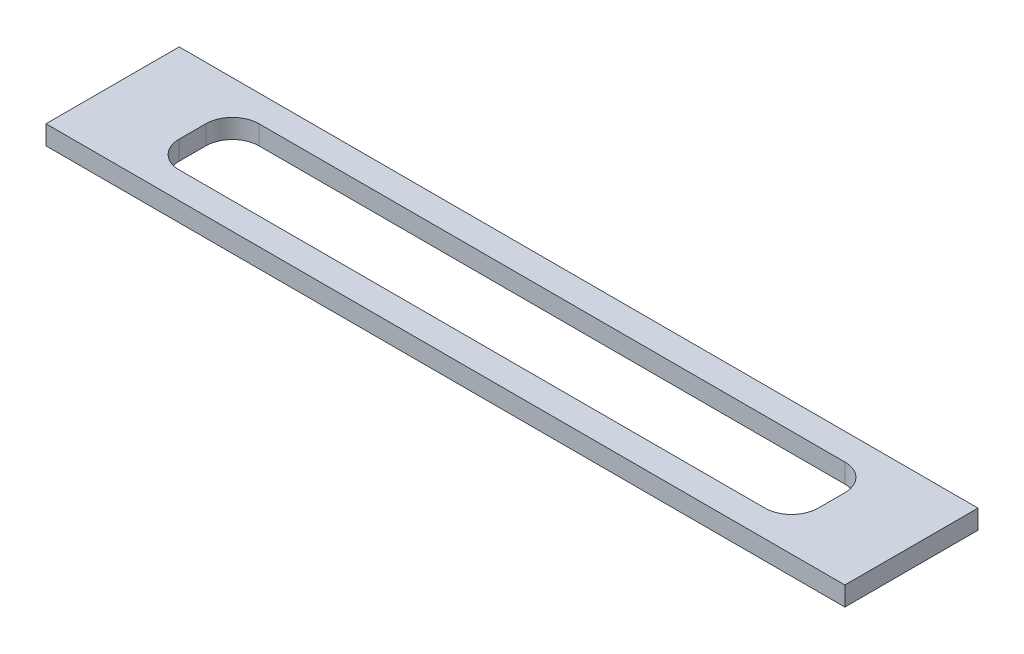
SolidWorks part; units mm, degrees
ref_plane "Front Plane" through (0, 0, 0) normal (0, 0, 1) x (1, 0, 0)
ref_plane "Top Plane" through (0, 0, 0) normal (0, 1, 0) x (1, 0, 0)
ref_plane "Right Plane" through (0, 0, 0) normal (1, 0, 0) x (0, 0, -1)
sketch "Sketch1" plane through (0, 0, 0) normal (0, 1, 0) x (1, 0, 0)
  line L1 (-691.8296, -43.3638) -> (70.1704, -43.3638)
  line L2 (-691.8296, -43.3638) -> (-691.8296, -170.3638)
  line L3 (-691.8296, -170.3638) -> (70.1704, -170.3638)
  line L4 (70.1704, -43.3638) -> (70.1704, -170.3638)
  dimension "D1" = 762
  dimension "D2" = 127
extrude "Boss-Extrude1" add sketch "Sketch1" along normal blind 18.288
sketch "Sketch3" plane through (0, 18.288, 0) normal (0, 1, 0) x (1, 0, 0)
  line L0 (70.1704, -43.3638) -> (-691.8296, -43.3638) construction
  line L1 (-615.6296, -144.9638) -> (-6.0296, -144.9638)
  line L2 (-615.6296, -144.9638) -> (-615.6296, -68.7638)
  line L3 (-615.6296, -68.7638) -> (-6.0296, -68.7638)
  line L4 (-6.0296, -144.9638) -> (-6.0296, -68.7638)
  line L5 (-615.6296, -144.9638) -> (-6.0296, -68.7638) construction
  line L6 (-615.6296, -68.7638) -> (-6.0296, -144.9638) construction
  line L8 (70.1704, -170.3638) -> (70.1704, -43.3638) construction
  point P0 (-310.8296, -106.8638)
  dimension "D1" = 63.5
  dimension "D2" = 76.2
  dimension "D3" = 609.6
  dimension "D4" = 76.2
extrude "Cut-Extrude1" cut sketch "Sketch3" against normal through all
fillet "Fillet1" radius 25.4 4 edges at (-6.0296, 9.144, 68.7638) (-6.0296, 9.144, 144.9638) (-615.6296, 9.144, 144.9638) (-615.6296, 9.144, 68.7638)
